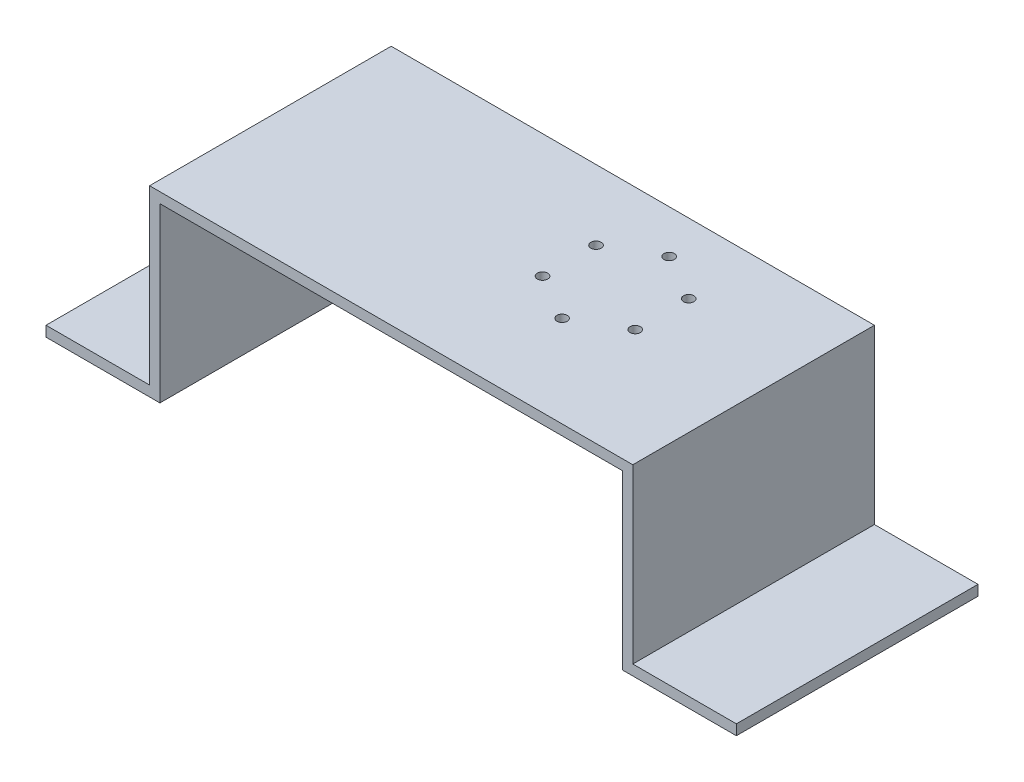
SolidWorks part; units mm, degrees
ref_plane "前视基准面" through (0, 0, 0) normal (0, 0, 1) x (1, 0, 0)
ref_plane "上视基准面" through (0, 0, 0) normal (0, 1, 0) x (1, 0, 0)
ref_plane "右视基准面" through (0, 0, 0) normal (1, 0, 0) x (0, 0, -1)
sketch "草图1" plane through (0, 0, 0) normal (0, 0, 1) x (1, 0, 0)
  line L0 (0, 0) -> (30, 0)
  line L1 (30, 0) -> (30, 50)
  line L2 (30, 50) -> (170, 50)
  line L3 (170, 50) -> (170, 0)
  line L4 (170, 0) -> (200, 0)
  line L5 (0, -3) -> (33, -3)
  line L6 (33, -3) -> (33, 47)
  line L7 (33, 47) -> (167, 47)
  line L8 (167, 47) -> (167, -3)
  line L9 (167, -3) -> (200, -3)
  line L10 (0, 0) -> (0, -3)
  line L11 (200, 0) -> (200, -3)
  dimension "D1" = 30
  dimension "D2" = 200
  dimension "D3" = 50
  dimension "D4" = 3
extrude "凸台-拉伸1" add sketch "草图1" along normal blind 70
sketch "草图2" plane through (0, 50, 0) normal (0, 1, 0) x (1, 0, 0)
  circle A0 centre (123.018, -43.5) radius 1.5 construction
  circle A1 centre (136.4414, -35.75) radius 1.5 construction
  circle A2 centre (136.4414, -20.25) radius 1.5 construction
  circle A3 centre (123.018, -12.5) radius 1.5 construction
  circle A4 centre (109.5946, -35.75) radius 1.5 construction
  circle A5 centre (109.5946, -20.25) radius 1.5 construction
  circle A6 centre (123.018, -43.5) radius 1.5
  circle A7 centre (136.4414, -35.75) radius 1.5
  circle A8 centre (136.4414, -20.25) radius 1.5
  circle A9 centre (123.018, -12.5) radius 1.5
  circle A10 centre (109.5946, -35.75) radius 1.5
  circle A11 centre (109.5946, -20.25) radius 1.5
extrude "切除-拉伸1" cut sketch "草图2" against normal blind 10
